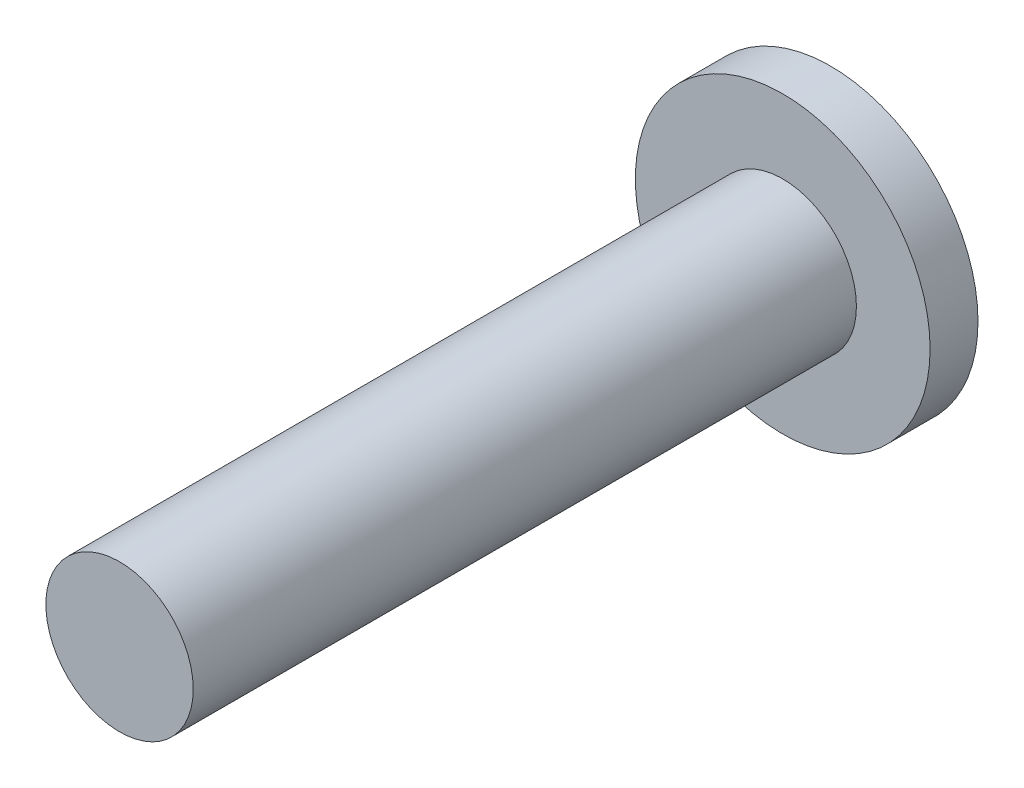
SolidWorks part; units mm, degrees
material "AISI 304"
ref_plane "前视基准面" through (0, 0, 0) normal (0, 0, 1) x (1, 0, 0)
ref_plane "上视基准面" through (0, 0, 0) normal (0, 1, 0) x (1, 0, 0)
ref_plane "右视基准面" through (0, 0, 0) normal (1, 0, 0) x (0, 0, -1)
other "Configuration Table"
sketch "草图1" plane through (0, 0, 0) normal (0, 0, 1) x (1, 0, 0)
  circle A0 centre (0, 0) radius 4
  dimension "D1" = 8
extrude "凸台-拉伸1" add sketch "草图1" along normal blind 1.3
sketch "草图2" plane through (0, 0, 1.3) normal (0, 0, 1) x (1, 0, 0)
  circle A0 centre (0, 0) radius 2
  dimension "D1" = 4
extrude "凸台-拉伸2" add sketch "草图2" along normal blind 18
sketch "草图3" plane through (0, 0, 0) normal (0, 0, -1) x (-1, 0, 0)
  line L1 (1.4434, 0) -> (0.7217, 1.25)
  line L2 (0.7217, 1.25) -> (-0.7217, 1.25)
  line L3 (-0.7217, 1.25) -> (-1.4434, 0)
  line L4 (-1.4434, 0) -> (-0.7217, -1.25)
  line L5 (-0.7217, -1.25) -> (0.7217, -1.25)
  line L6 (0.7217, -1.25) -> (1.4434, 0)
  circle A0 centre (0, 0) radius 1.25 construction
extrude "切除-拉伸1" cut sketch "草图3" against normal blind 1
